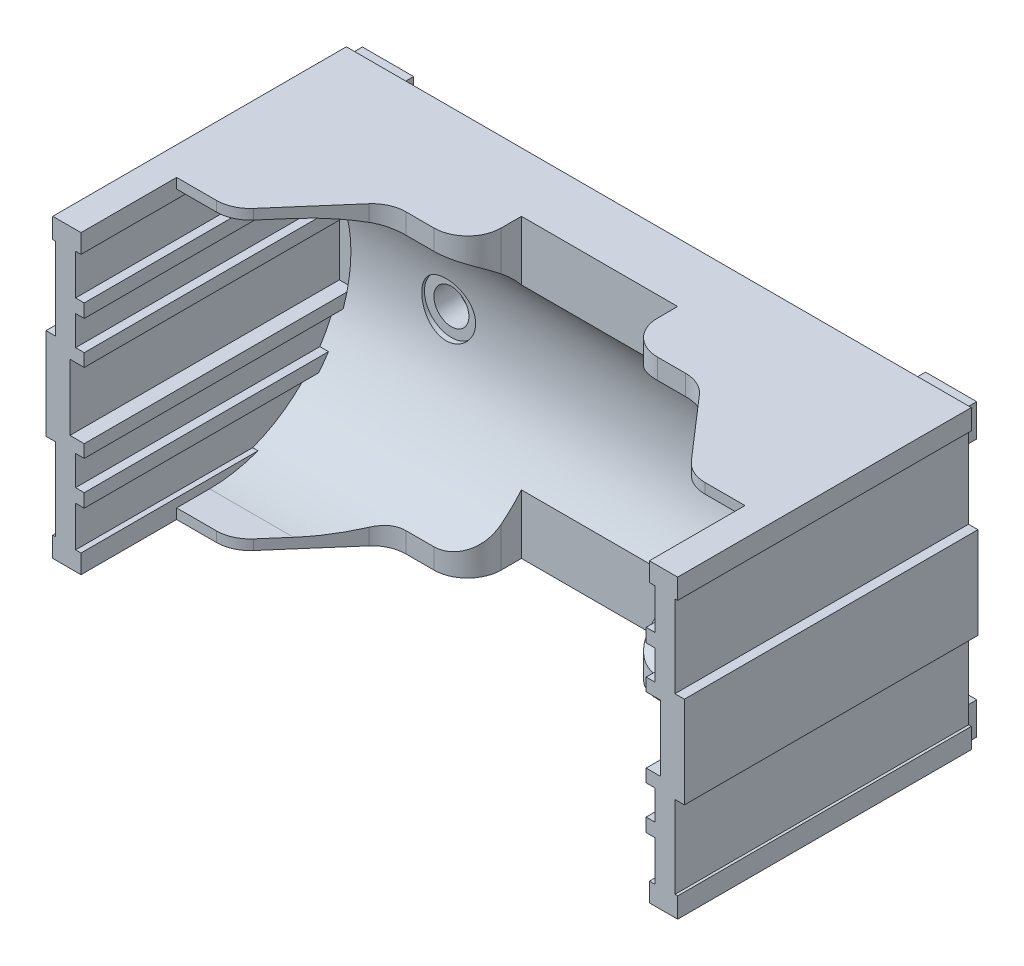
SolidWorks part; units mm, degrees
ref_plane "Front Plane" through (0, 0, 0) normal (0, 0, 1) x (1, 0, 0)
ref_plane "Top Plane" through (0, 0, 0) normal (0, 1, 0) x (1, 0, 0)
ref_plane "Right Plane" through (0, 0, 0) normal (1, 0, 0) x (0, 0, -1)
sketch "Sketch1" plane through (0, 0, 0) normal (0, 0, 1) x (1, 0, 0)
  line L0 (-29.21, -13.97) -> (29.21, 13.97) construction
  line L1 (-29.21, 13.97) -> (29.21, 13.97)
  line L2 (-29.21, 13.97) -> (-29.21, -13.97)
  line L3 (-29.21, -13.97) -> (29.21, -13.97)
  line L4 (29.21, 13.97) -> (29.21, -13.97)
  point P4 (0, 0)
  dimension "D1" = 58.42
  dimension "D2" = 27.94
extrude "Boss-Extrude1" add sketch "Sketch1" along normal blind 27.686
sketch "Sketch2" plane through (0, 0, 27.686) normal (0, 0, 1) x (1, 0, 0)
  line L0 (-29.21, 13.97) -> (-29.21, -13.97) construction
  line L1 (-29.21, 4.318) -> (-30.099, 4.318)
  line L2 (-29.21, 4.318) -> (-29.21, -4.318)
  line L3 (-29.21, -4.318) -> (-30.099, -4.318)
  line L4 (-30.099, 4.318) -> (-30.099, -4.318)
  line L5 (29.21, 0) -> (-29.21, 0) construction
  line L6 (-29.21, 13.97) -> (-29.464, 13.97)
  line L7 (-29.21, 13.97) -> (-29.21, 12.065)
  line L8 (-29.21, 12.065) -> (-29.464, 12.065)
  line L9 (-29.464, 13.97) -> (-29.464, 12.065)
  line L10 (0, 13.97) -> (0, -13.97) construction
  line L11 (29.21, 13.97) -> (-29.21, 13.97) construction
  line L12 (-29.21, -13.97) -> (29.21, -13.97) construction
  line L13 (29.21, -13.97) -> (29.21, 13.97) construction
  line L14 (-29.464, -13.97) -> (-29.464, -12.065)
  line L15 (-29.21, -12.065) -> (-29.464, -12.065)
  line L16 (-29.21, -13.97) -> (-29.21, -12.065)
  line L17 (-29.21, -13.97) -> (-29.464, -13.97)
  line L18 (29.21, -13.97) -> (29.464, -13.97)
  line L19 (29.21, -13.97) -> (29.21, -12.065)
  line L20 (29.21, -12.065) -> (29.464, -12.065)
  line L21 (29.464, -13.97) -> (29.464, -12.065)
  line L22 (29.464, 13.97) -> (29.464, 12.065)
  line L23 (29.21, 12.065) -> (29.464, 12.065)
  line L24 (29.21, 13.97) -> (29.21, 12.065)
  line L25 (29.21, 13.97) -> (29.464, 13.97)
  line L26 (30.099, 4.318) -> (30.099, -4.318)
  line L27 (29.21, -4.318) -> (30.099, -4.318)
  line L28 (29.21, 4.318) -> (29.21, -4.318)
  line L29 (29.21, 4.318) -> (30.099, 4.318)
  point P19 (-29.21, 0)
  dimension "D1" = 8.636
  dimension "D2" = 0.889
  dimension "D3" = 0.254
  dimension "D4" = 1.905
extrude "Boss-Extrude3" add sketch "Sketch2" against normal up to vertex (27.686 mm away)
sketch "Sketch4" plane through (0, 0, 0) normal (1, 0, 0) x (0, 0, -1)
  line L0 (-15.5575, 13.0175) -> (-27.686, 13.0175)
  line L1 (-27.686, 12.065) -> (-27.686, 13.97) construction
  line L2 (-27.686, 13.0175) -> (-27.686, -13.0175)
  line L3 (-27.686, -13.97) -> (-27.686, -12.065) construction
  line L4 (-27.686, -13.0175) -> (-15.5575, -13.0175)
  line L5 (0, 0) -> (-27.686, 0) construction
  line L6 (0, -4.318) -> (0, 4.318) construction
  arc A0 (-15.5575, 13.0175) -> (-15.5575, -13.0175) centre (-15.5575, 0) cw
  dimension "D2" = 2.54
  dimension "D1" = 26.035
extrude "Cut-Extrude1" cut sketch "Sketch4" against normal mid plane 54.61
sketch "Sketch5" plane through (0, -13.97, 0) normal (0, -1, 0) x (1, 0, 0)
  line L0 (-27.305, 27.686) -> (-27.305, 18.669)
  line L1 (-27.305, 27.686) -> (-27.305, 15.5575) construction
  line L2 (-27.305, 18.669) -> (-23.0377, 18.669)
  line L3 (-20.6407, 17.576) -> (-15.5897, 11.761)
  line L4 (-13.1927, 10.668) -> (-10.541, 10.668)
  line L5 (-7.366, 7.493) -> (-7.366, 5.588)
  line L7 (-7.366, 5.588) -> (7.366, 5.588)
  line L8 (0, 0) -> (0, 27.686) construction
  line L9 (-29.464, 27.686) -> (29.464, 27.686) construction
  line L10 (-29.464, 0) -> (29.464, 0) construction
  line L11 (-27.305, 27.686) -> (27.305, 27.686)
  line L12 (7.366, 7.493) -> (7.366, 5.588)
  line L13 (13.1927, 10.668) -> (10.541, 10.668)
  line L14 (20.6407, 17.576) -> (15.5897, 11.761)
  line L15 (27.305, 18.669) -> (23.0377, 18.669)
  line L16 (27.305, 27.686) -> (27.305, 18.669)
  arc A0 (-7.366, 7.493) -> (-10.541, 10.668) centre (-10.541, 7.493) ccw
  arc A1 (-13.1927, 10.668) -> (-15.5897, 11.761) centre (-13.1927, 13.843) cw
  arc A2 (-20.6407, 17.576) -> (-23.0377, 18.669) centre (-23.0377, 15.494) ccw
  arc A3 (20.6407, 17.576) -> (23.0377, 18.669) centre (23.0377, 15.494) cw
  arc A4 (13.1927, 10.668) -> (15.5897, 11.761) centre (13.1927, 13.843) ccw
  arc A5 (7.366, 7.493) -> (10.541, 10.668) centre (10.541, 7.493) cw
  point P25 (-21.59, 18.669)
  point P37 (0, 5.588)
  point P38 (21.59, 18.669)
  dimension "D5" = 3.175
  dimension "D1" = 14.732
  dimension "D2" = 10.668
  dimension "D3" = 18.669
  dimension "D4" = 43.18
  dimension "D6" = 5.588
extrude "Cut-Extrude3" cut sketch "Sketch5" against normal through all
sketch "Sketch6" plane through (0, 0, 27.686) normal (0, 0, 1) x (1, 0, 0)
  line L0 (-27.305, -13.0175) -> (-27.305, 13.0175) construction
  line L1 (-27.305, 13.97) -> (-26.797, 13.97)
  line L2 (-27.305, 13.97) -> (-27.305, 12.192)
  line L3 (-27.305, 12.192) -> (-26.797, 12.192)
  line L4 (-26.797, 13.97) -> (-26.797, 12.192)
  line L5 (-27.305, 8.382) -> (-26.4922, 8.382)
  line L6 (-27.305, 8.382) -> (-27.305, 7.112)
  line L7 (-27.305, 7.112) -> (-26.4922, 7.112)
  line L8 (-26.4922, 8.382) -> (-26.4922, 7.112)
  line L10 (-27.305, 13.97) -> (-27.305, -13.97) construction
  line L11 (-27.305, 4.318) -> (-26.4922, 4.318)
  line L12 (-27.305, 4.318) -> (-27.305, -4.318)
  line L13 (-27.305, -4.318) -> (-26.4922, -4.318)
  line L14 (-30.099, 0) -> (30.099, 0) construction
  line L15 (-30.099, 4.318) -> (-30.099, -4.318) construction
  line L16 (30.099, -4.318) -> (30.099, 4.318) construction
  line L17 (0, 13.97) -> (0, -13.97) construction
  line L18 (-7.366, 13.97) -> (7.366, 13.97) construction
  line L19 (-7.366, -13.97) -> (7.366, -13.97) construction
  line L20 (-29.464, 13.97) -> (-29.464, 12.065) construction
  line L22 (-26.4922, 4.318) -> (-26.4922, -4.318)
  line L23 (-29.21, 4.318) -> (-30.099, 4.318) construction
  line L24 (-26.4922, -8.382) -> (-26.4922, -7.112)
  line L25 (-27.305, -7.112) -> (-26.4922, -7.112)
  line L26 (-27.305, -8.382) -> (-27.305, -7.112)
  line L27 (-27.305, -8.382) -> (-26.4922, -8.382)
  line L28 (-26.797, -13.97) -> (-26.797, -12.192)
  line L29 (-27.305, -12.192) -> (-26.797, -12.192)
  line L30 (-27.305, -13.97) -> (-27.305, -12.192)
  line L31 (-27.305, -13.97) -> (-26.797, -13.97)
  line L32 (27.305, -13.97) -> (26.797, -13.97)
  line L33 (27.305, -13.97) -> (27.305, -12.192)
  line L34 (27.305, -12.192) -> (26.797, -12.192)
  line L35 (26.797, -13.97) -> (26.797, -12.192)
  line L36 (27.305, -8.382) -> (26.4922, -8.382)
  line L37 (27.305, -8.382) -> (27.305, -7.112)
  line L38 (27.305, -7.112) -> (26.4922, -7.112)
  line L39 (26.4922, -8.382) -> (26.4922, -7.112)
  line L40 (26.4922, 4.318) -> (26.4922, -4.318)
  line L41 (27.305, -4.318) -> (26.4922, -4.318)
  line L42 (27.305, 4.318) -> (27.305, -4.318)
  line L43 (27.305, 4.318) -> (26.4922, 4.318)
  line L44 (26.4922, 8.382) -> (26.4922, 7.112)
  line L45 (27.305, 7.112) -> (26.4922, 7.112)
  line L46 (27.305, 8.382) -> (27.305, 7.112)
  line L47 (27.305, 8.382) -> (26.4922, 8.382)
  line L48 (26.797, 13.97) -> (26.797, 12.192)
  line L49 (27.305, 12.192) -> (26.797, 12.192)
  line L50 (27.305, 13.97) -> (27.305, 12.192)
  line L51 (27.305, 13.97) -> (26.797, 13.97)
  point P31 (-27.305, 0)
  dimension "D1" = 2.667
  dimension "D2" = 1.778
  dimension "D3" = 1.27
  dimension "D4" = 3.6068
  dimension "D5" = 2.794
extrude "Boss-Extrude4" add sketch "Sketch6" against normal blind 27.686
sketch "Sketch7" plane through (0, 0, 27.686) normal (0, 0, 1) x (1, 0, 0)
  line L0 (-26.4922, -4.318) -> (-26.4922, 4.318) construction
  line L1 (-26.4922, 3.1115) -> (-27.8384, 3.1115)
  line L2 (-26.4922, 3.1115) -> (-26.4922, -3.1115)
  line L3 (-26.4922, -3.1115) -> (-27.8384, -3.1115)
  line L4 (-27.8384, 3.1115) -> (-27.8384, -3.1115)
  line L5 (-30.099, 0) -> (30.099, 0) construction
  line L6 (-30.099, 4.318) -> (-30.099, -4.318) construction
  line L7 (30.099, -4.318) -> (30.099, 4.318) construction
  line L8 (0, 13.97) -> (0, -13.97) construction
  line L9 (-7.366, 13.97) -> (7.366, 13.97) construction
  line L10 (-7.366, -13.97) -> (7.366, -13.97) construction
  line L11 (27.8384, 3.1115) -> (27.8384, -3.1115)
  line L12 (26.4922, -3.1115) -> (27.8384, -3.1115)
  line L13 (26.4922, 3.1115) -> (26.4922, -3.1115)
  line L14 (26.4922, 3.1115) -> (27.8384, 3.1115)
  point P18 (-27.8384, 0)
  dimension "D1" = 6.223
  dimension "D2" = 1.3462
extrude "Cut-Extrude4" cut sketch "Sketch7" against normal blind 25.4
sketch "Sketch8" plane through (0, 0, 27.686) normal (0, 0, 1) x (1, 0, 0)
  line L0 (0, 13.97) -> (0, -13.97) construction
  line L1 (-7.366, 13.97) -> (7.366, 13.97) construction
  line L2 (-7.366, -13.97) -> (7.366, -13.97) construction
  line L3 (-30.099, 0) -> (30.099, 0) construction
  line L4 (-30.099, 4.318) -> (-30.099, -4.318) construction
  line L5 (30.099, -4.318) -> (30.099, 4.318) construction
  circle A0 centre (-17.272, 0) radius 1.651
  circle A1 centre (17.272, 0) radius 1.651
  dimension "D1" = 3.302
  dimension "D2" = 34.544
extrude "Cut-Extrude5" cut sketch "Sketch8" against normal through all
sketch "Sketch9" plane through (0, 0, 27.686) normal (0, 0, 1) x (1, 0, 0)
  circle A0 centre (-17.272, 0) radius 2.54
  circle A1 centre (17.272, 0) radius 2.54
  dimension "D1" = 5.08
extrude "Cut-Extrude6" cut sketch "Sketch9" against normal blind 25.4
sketch "Sketch10" plane through (0, 0, 0) normal (0, 0, -1) x (-1, 0, 0)
  line L0 (-28.9637, 10.6474) -> (-28.9637, 13.6954)
  line L1 (-28.9637, 13.6954) -> (-24.1377, 13.6954)
  line L2 (-24.1377, 13.6954) -> (-24.1377, 12.4254)
  line L3 (-24.1377, 12.4254) -> (-27.6937, 12.4254)
  line L4 (-27.6937, 12.4254) -> (-27.6937, 10.6474)
  line L5 (-27.6937, 10.6474) -> (-28.9637, 10.6474)
  dimension "D1" = 1.27
  dimension "D2" = 3.048
  dimension "D3" = 4.826
extrude "Boss-Extrude5" add sketch "Sketch10" along normal blind 1.016
mirror "Mirror2" about plane through (0, 0, 0) normal (0, 1, 0) of "Boss-Extrude5"
mirror "Mirror3" about plane through (0, 0, 0) normal (1, 0, 0) of "Mirror2", "Boss-Extrude5"
